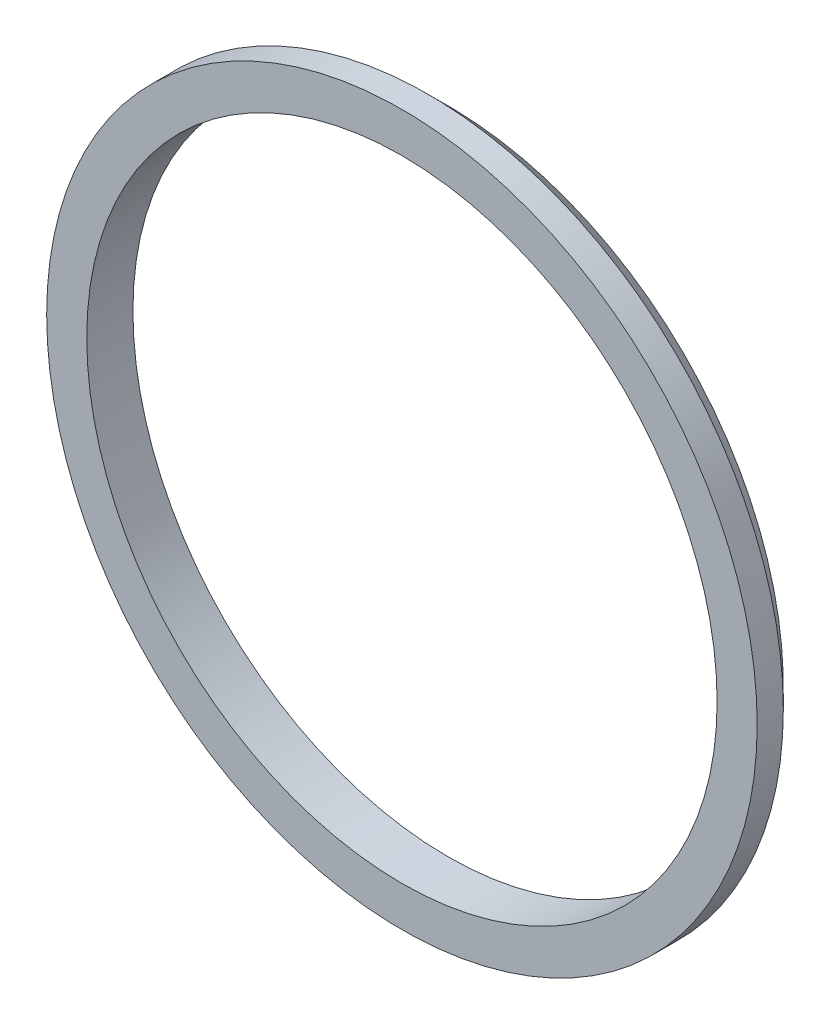
SolidWorks part; units mm, degrees
material "6061-T6 (SS)"
ref_plane "Front Plane" through (0, 0, 0) normal (0, 0, 1) x (1, 0, 0)
ref_plane "Top Plane" through (0, 0, 0) normal (0, 1, 0) x (1, 0, 0)
ref_plane "Right Plane" through (0, 0, 0) normal (1, 0, 0) x (0, 0, -1)
sketch "Sketch4" plane through (0, 0, 0) normal (0, 1, 0) x (1, 0, 0)
  line L0 (100.366, 0) -> (94.366, 0)
  line L1 (-100.366, 0) -> (100.366, 0) construction
  line L2 (94.366, 0) -> (94.366, -13.825)
  line L3 (0, -17) -> (155.2172, -17) construction
  line L5 (94.366, -13.825) -> (100.366, -13.825)
  line L6 (100.366, -13.825) -> (100.366, 0) construction
  line L7 (106.366, -6) -> (100.366, 0)
  line L8 (106.366, -6) -> (106.366, -13.825)
  line L9 (106.366, -13.825) -> (100.366, -13.825)
  line L10 (0, 0) -> (0, -72.5185) construction
  dimension "D1" = 6.35
  dimension "D2" = 45
revolve "Revolve1" add sketch "Sketch4" angle 360 about L10
